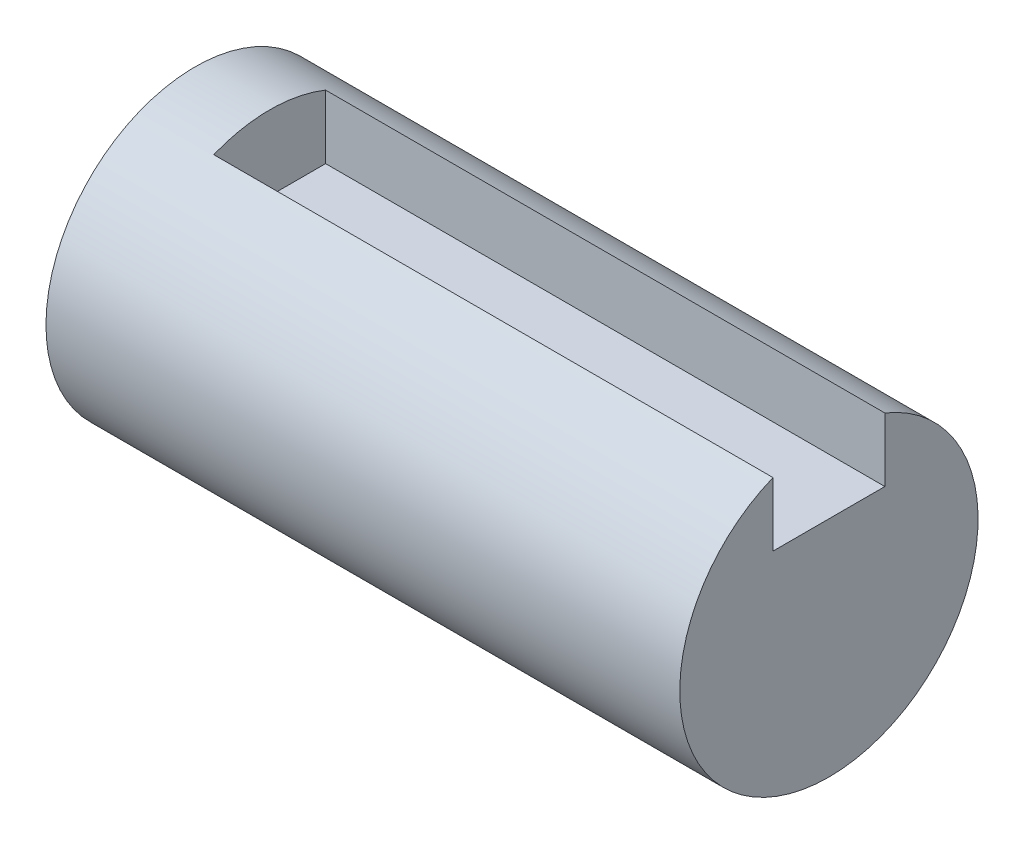
SolidWorks part; units mm, degrees
ref_plane "前视基准面" through (0, 0, 0) normal (0, 0, 1) x (1, 0, 0)
ref_plane "上视基准面" through (0, 0, 0) normal (0, 1, 0) x (1, 0, 0)
ref_plane "右视基准面" through (0, 0, 0) normal (1, 0, 0) x (0, 0, -1)
other "Configuration Table"
sketch "草图1" plane through (0, 0, 0) normal (1, 0, 0) x (0, 0, -1)
  circle A0 centre (0, 0) radius 4
extrude "凸台-拉伸1" add sketch "草图1" along normal blind 17
sketch "草图2" plane through (17, 0, 0) normal (1, 0, 0) x (0, 0, -1)
  line L0 (-5.9164, 0) -> (5.9164, 0) construction
  line L1 (0, -4.2751) -> (0, 4.2751) construction
  line L2 (-1.5, 2) -> (1.5, 2)
  line L3 (-1.5, 2) -> (-1.5, 3.7081)
  line L4 (1.5, 2) -> (1.5, 3.7081)
  circle A0 centre (0, 0) radius 4 construction
  circle A1 centre (0, 0) radius 4
  point P4 (0, 0)
  point P8 (0, 0)
  circle M6 centre (0, 0) radius 4
  dimension "D1" = 2
  dimension "D2" = 3
extrude "切除-拉伸1" cut sketch "草图2" against normal blind 15 contours L2 L4 L3 M6
